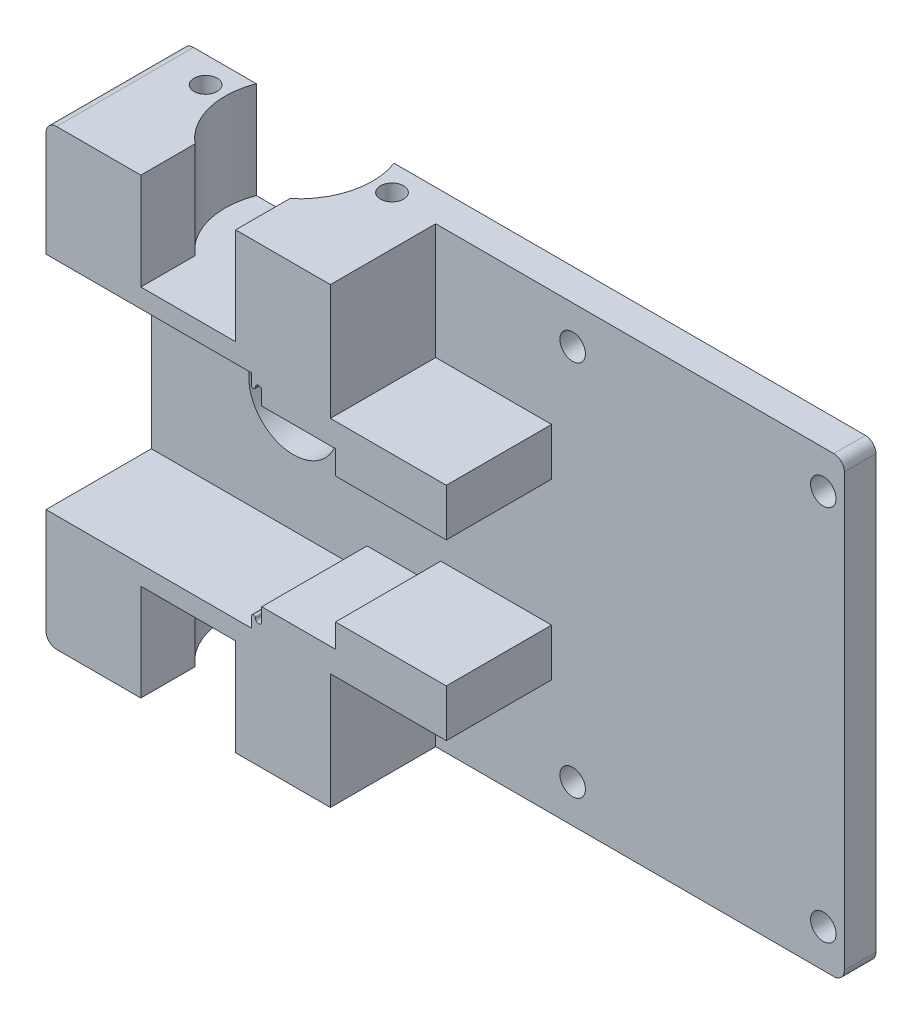
SolidWorks part; units mm, degrees
ref_plane "Přední rovina" through (0, 0, 0) normal (0, 0, 1) x (1, 0, 0)
ref_plane "Horní rovina" through (0, 0, 0) normal (0, 1, 0) x (1, 0, 0)
ref_plane "Pravá rovina" through (0, 0, 0) normal (1, 0, 0) x (0, 0, -1)
sketch "Skica2" plane through (0, 0, 0) normal (0, 0, 1) x (1, 0, 0)
  line L1 (2, 0) -> (129.6, 0)
  line L2 (0, 2) -> (0, 84)
  line L3 (2, 86) -> (129.6, 86)
  line L4 (131.6, 2) -> (131.6, 84)
  arc A0 (129.6, 86) -> (131.6, 84) centre (129.6, 84) cw
  arc A1 (129.6, 0) -> (131.6, 2) centre (129.6, 2) ccw
  arc A2 (2, 0) -> (0, 2) centre (2, 2) cw
  arc A3 (0, 84) -> (2, 86) centre (2, 84) cw
  point P7 (131.6, 86)
  point P12 (0, 0)
  point P15 (0, 86)
  dimension "D3" = 2
  dimension "D1" = 86
  dimension "D2" = 131.6
extrude "Přidat vysunutím1" add sketch "Skica2" along normal blind 6
sketch "Skica3" plane through (0, 0, 6) normal (0, 0, 1) x (1, 0, 0)
  line L0 (0, 84) -> (0, 2) construction
  line L1 (0, 43) -> (131.6, 43) construction
  line L2 (131.6, 2) -> (131.6, 84) construction
  line L3 (129.6, 86) -> (2, 86) construction
  line L4 (2, 0) -> (129.6, 0) construction
  line L5 (54, 86) -> (54, 0) construction
  circle A0 centre (27, 43) radius 8.5
  circle A1 centre (127.6, 78.8) radius 2.425
  circle A3 centre (80, 7.2) radius 2.425
  circle A4 centre (127.6, 7.2) radius 2.425
  circle A6 centre (80, 78.8) radius 2.425
  point P2 (0, 43)
  point P23 (54, 43)
  point P24 (54, 86)
  dimension "D1" = 17
  dimension "D3" = 4.85
  dimension "D4" = 71.6
  dimension "D6" = 4
  dimension "D2" = 27
  dimension "D5" = 47.6
  dimension "D7" = 54
extrude "Odebrat vysunutím1" cut sketch "Skica3" against normal blind 6
sketch "Skica4" plane through (0, 0, 6) normal (0, 0, 1) x (1, 0, 0)
  line L1 (2, 86) -> (54, 86)
  line L2 (0, 84) -> (0, 64)
  line L5 (2, 0) -> (54, 0)
  line L6 (0, 2) -> (0, 22)
  line L9 (0, 84) -> (0, 2) construction
  line L10 (129.6, 86) -> (2, 86) construction
  line L11 (2, 0) -> (129.6, 0) construction
  line L15 (0, 22) -> (54, 22)
  line L16 (54, 22) -> (54, 0)
  line L17 (54, 64) -> (0, 64)
  line L18 (54, 64) -> (54, 86)
  arc A0 (2, 86) -> (0, 84) centre (2, 84) ccw
  arc A1 (2, 0) -> (0, 2) centre (2, 2) cw
  point P18 (0, 86)
  point P21 (0, 0)
  point P24 (54, 64)
  dimension "D3" = 2
  dimension "D1" = 54
  dimension "D2" = 22
extrude "Přidat vysunutím3" add sketch "Skica4" along normal blind 20
sketch "Skica6" plane through (0, 0, 0) normal (0, -1, 0) x (1, 0, 0)
  line L0 (2, 0) -> (129.6, 0) construction
  line L1 (0, 26) -> (0, 0) construction
  line L3 (2, 26) -> (54, 26) construction
  circle A0 centre (27, 5) radius 14
  point P4 (0, 0)
  point P5 (27, 5)
  point P7 (27, 26)
  dimension "D1" = 28
  dimension "D2" = 5
  dimension "D3" = 27
extrude "Odebrat vysunutím2" cut sketch "Skica6" against normal blind 18.4
sketch "Skica10" plane through (0, 86, 0) normal (0, 1, 0) x (1, 0, 0)
  line L1 (129.6, 0) -> (2, 0) construction
  line L2 (0, -26) -> (0, 0) construction
  line L3 (54, -26) -> (2, -26) construction
  circle A0 centre (27, -5) radius 14
  point P0 (27, -26)
  dimension "D1" = 28
  dimension "D2" = 5
  dimension "D3" = 27
extrude "Odebrat vysunutím3" cut sketch "Skica10" against normal blind 18.4
sketch "Skica18" plane through (0, 0, 6) normal (0, 0, 1) x (1, 0, 0)
  line L0 (54, 22) -> (0, 22) construction
  line L1 (54, 64) -> (39, 64)
  line L2 (54, 64) -> (54, 22)
  line L3 (54, 22) -> (39, 22)
  line L4 (39, 64) -> (39, 22)
  dimension "D1" = 15
extrude "Přidat vysunutím5" add sketch "Skica18" along normal blind 20
sketch "Skica21" plane through (0, 0, 26) normal (0, 0, 1) x (1, 0, 0)
  line L2 (39, 24) -> (39, 62)
  line L3 (39, 64) -> (39, 22) construction
  line L4 (39, 62) -> (40.96, 62) construction
  line L5 (39, 62) -> (40.96, 62) construction
  line L6 (39, 24) -> (40.96, 24) construction
  line L7 (40.96, 24) -> (40.96, 62)
  arc A0 (40.96, 62) -> (39.76, 62) centre (40.36, 62) ccw
  arc A1 (39.76, 62) -> (39, 62) centre (39.38, 62) cw
  arc A2 (40.96, 24) -> (39.76, 24) centre (40.36, 24) cw
  arc A3 (39.76, 24) -> (39, 24) centre (39.38, 24) ccw
  dimension "D3" = 0.6
  dimension "D4" = 0.38
  dimension "D1" = 2
  dimension "D2" = 2
  dimension "D5" = 1.96
extrude "Odebrat vysunutím9" cut sketch "Skica21" against normal blind 20
sketch "Skica14" plane through (0, 0, 0) normal (0, -1, 0) x (1, 0, 0)
  line L1 (27, -6.8271) -> (27, 37.6955) construction
  circle A0 centre (9.3, 5) radius 2.2
  circle A1 centre (44.7, 5) radius 2.2
  point P6 (27, 5)
  dimension "D1" = 4.4
  dimension "D2" = 35.4
extrude "Odebrat vysunutím7" cut sketch "Skica14" against normal blind 5
sketch "Skica15" plane through (0, 86, 0) normal (0, 1, 0) x (1, 0, 0)
  line L1 (27, -26.3528) -> (27, 14.4318) construction
  circle A0 centre (9.3, -5) radius 2.2
  circle A1 centre (44.7, -5) radius 2.2
  point P4 (27, -5)
  point P7 (0, 0)
  point P8 (0, 0)
  dimension "D1" = 4.4
  dimension "D2" = 35.4
extrude "Odebrat vysunutím8" cut sketch "Skica15" against normal blind 5
sketch "Skica22" plane through (0, 0, 0) normal (0, 0, -1) x (-1, 0, 0)
  line L0 (-127.6, 78.8) -> (-80, 78.8) construction
  line L1 (-80, 78.8) -> (-80, 7.2) construction
  point P4 (-80, 43)
  point P7 (-103.8, 78.8)
  point P8 (0, 0)
sketch "Skica23" plane through (0, 0, 0) normal (0, 0, -1) x (-1, 0, 0)
  line L0 (-118.8, 55.2) -> (-88.8, 30.8) construction
  line L1 (-88.8, 55.2) -> (-118.8, 30.8) construction
  circle A0 centre (-118.8, 55.2) radius 2.2
  circle A1 centre (-88.8, 55.2) radius 2.2
  circle A2 centre (-88.8, 30.8) radius 2.2
  circle A3 centre (-118.8, 30.8) radius 2.2
  point P8 (-103.8, 43)
  dimension "D1" = 4.4
  dimension "D2" = 24.4
  dimension "D3" = 30
extrude "Odebrat vysunutím10" cut sketch "Skica23" against normal blind 4
sketch "Skica24" plane through (0, 86, 0) normal (0, 1, 0) x (1, 0, 0)
  line L0 (54, -26) -> (2, -26) construction
  line L1 (18, -26) -> (36, -26)
  line L2 (18, -26) -> (18, -15.7238)
  line L3 (18, -15.7238) -> (36, -15.7238)
  line L4 (36, -26) -> (36, -15.7238)
  arc A0 (13.9233, 0) -> (40.0767, 0) centre (27, -5) ccw construction
  point P9 (27, -5)
  point P10 (27, -15.7238)
  point P12 (0, 0)
  dimension "D1" = 18
extrude "Odebrat vysunutím12" cut sketch "Skica24" against normal blind 18.4
sketch "Skica31" plane through (0, 0, 6) normal (0, 0, 1) x (1, 0, 0)
  line L0 (39, 64) -> (54, 64) construction
  line L1 (54, 0) -> (54, 86) construction
  line L2 (39, 22) -> (54, 22) construction
  line L3 (54, 0) -> (54, 86) construction
  line L5 (54, 64) -> (76, 64)
  line L6 (54, 64) -> (54, 22)
  line L7 (54, 22) -> (76, 22)
  line L8 (76, 64) -> (76, 22)
  dimension "D1" = 4
extrude "Přidat vysunutím6" add sketch "Skica31" along normal blind 20
sketch "Skica25" plane through (0, 0, 0) normal (0, -1, 0) x (1, 0, 0)
  line L0 (2, 26) -> (54, 26) construction
  line L1 (18, 26) -> (36, 26)
  line L2 (18, 26) -> (18, 15.7238)
  line L3 (18, 15.7238) -> (36, 15.7238)
  line L4 (36, 26) -> (36, 15.7238)
  arc A0 (40.0767, 0) -> (13.9233, 0) centre (27, 5) ccw construction
  arc A1 (40.0767, 0) -> (13.9233, 0) centre (27, 5) ccw construction
  point P9 (0, 0)
  point P10 (0, 0)
  dimension "D1" = 18
extrude "Odebrat vysunutím13" cut sketch "Skica25" against normal blind 18.4
sketch "Skica26" plane through (40.96, 0, 0) normal (-1, 0, 0) x (0, 0, 1)
  line L0 (26, 24) -> (26, 62) construction
  line L1 (26, 55) -> (6, 55)
  line L2 (26, 55) -> (26, 31)
  line L3 (26, 31) -> (6, 31)
  line L4 (6, 55) -> (6, 31)
  line L5 (6, 24) -> (6, 62) construction
  point P8 (26, 43)
  point P9 (26, 43)
  dimension "D1" = 24
extrude "Odebrat vysunutím14" cut sketch "Skica26" against normal blind 36.4
sketch "Skica27" plane through (40.96, 0, 0) normal (-1, 0, 0) x (0, 0, 1)
  line L6 (26, 55) -> (26, 62) construction
  line L7 (26, 59.5) -> (6, 59.5)
  line L8 (26, 59.5) -> (26, 26.5)
  line L9 (26, 26.5) -> (6, 26.5)
  line L10 (6, 59.5) -> (6, 26.5)
  line L11 (6, 24) -> (6, 31) construction
  point P8 (6, 43)
  point P9 (0, 0)
  dimension "D1" = 33
extrude "Odebrat vysunutím15" cut sketch "Skica27" against normal blind 14
sketch "Skica32" plane through (54.96, 0, 0) normal (-1, 0, 0) x (0, 0, 1)
  line L0 (26, 55) -> (6, 55) construction
  line L1 (26, 55) -> (26, 59.5) construction
  circle A0 centre (16, 57.25) radius 0.9653
  point P0 (16, 55)
  point P1 (26, 57.25)
